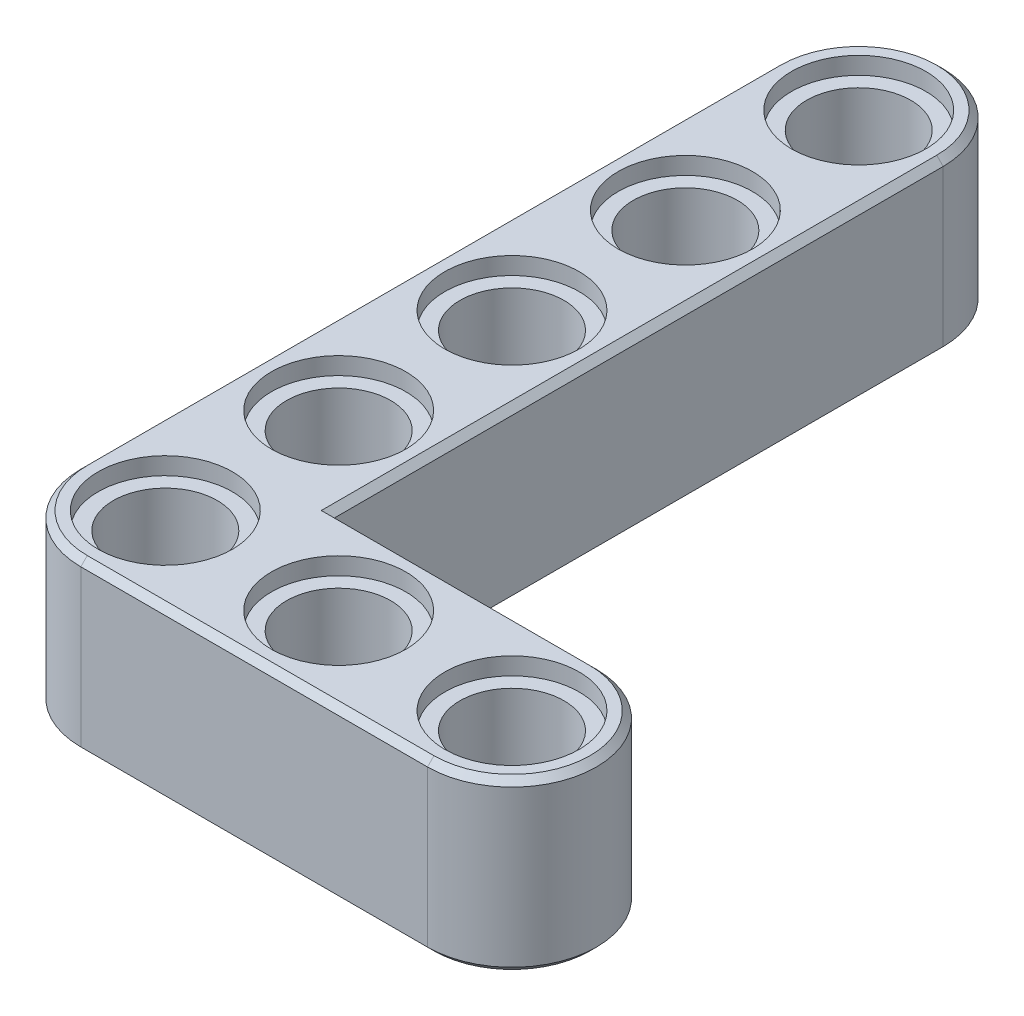
SolidWorks part; units mm, degrees
ref_plane "Front Plane" through (0, 0, 0) normal (0, 0, 1) x (1, 0, 0)
ref_plane "Top Plane" through (0, 0, 0) normal (0, 1, 0) x (1, 0, 0)
ref_plane "Right Plane" through (0, 0, 0) normal (1, 0, 0) x (0, 0, -1)
sketch "Sketch1" plane through (0, 0, 0) normal (0, 1, 0) x (1, 0, 0)
  line L0 (0, 0) -> (16, 0) construction
  line L1 (0, 0) -> (0, 32) construction
  line L2 (3.9, 3.9) -> (16, 3.9)
  line L3 (3.9, 3.9) -> (3.9, 32)
  line L4 (-3.9, -3.9) -> (16, -3.9)
  line L5 (-3.9, -3.9) -> (-3.9, 32)
  arc A0 (16, 3.9) -> (16, -3.9) centre (16, 0) cw
  arc A1 (3.9, 32) -> (-3.9, 32) centre (0, 32) ccw
  dimension "D1" = 16
  dimension "D2" = 32
  dimension "D3" = 3.9
  dimension "D4" = 3.9
extrude "Boss-Extrude1" add sketch "Sketch1" along normal mid plane 7.8
fillet "Fillet1" radius 3.9 1 edges at (-3.9, 0, 3.9)
sketch "Sketch2" plane through (0, 3.9, 0) normal (0, 1, 0) x (1, 0, 0)
  circle A0 centre (0, 0) radius 2.4
  dimension "D1" = 4.8
extrude "Cut-Extrude2" cut sketch "Sketch2" against normal through all
sketch "Sketch4" plane through (0, 3.9, 0) normal (0, 1, 0) x (1, 0, 0)
  circle A0 centre (0, 0) radius 3.1
  dimension "D1" = 6.2
extrude "Cut-Extrude3" cut sketch "Sketch4" against normal blind 0.8
mirror "Mirror1" about plane through (0, 0, 0) normal (0, 1, 0) of "Cut-Extrude3"
pattern_linear "LPattern1" count 5 spacing 8 along (0, 0, -1) of "Mirror1", "Cut-Extrude2", "Cut-Extrude3"
pattern_linear "LPattern2" count 3 spacing 8 along (1, 0, 0) of "Mirror1", "Cut-Extrude3", "Cut-Extrude2"
chamfer "Chamfer1" distance 0.3 angle 45 14 edges at (9.95, 3.9, -3.9) (19.9, 3.9, 0) (3.9, 3.9, -17.95) (8, 3.9, 3.9) (0, 3.9, -35.9) (-2.7577, 3.9, 2.7577) (-3.9, 3.9, -16) (3.9, -3.9, -17.95) (0, -3.9, -35.9) (-3.9, -3.9, -16) (9.95, -3.9, -3.9) (-2.7577, -3.9, 2.7577) (19.9, -3.9, 0) (8, -3.9, 3.9)
